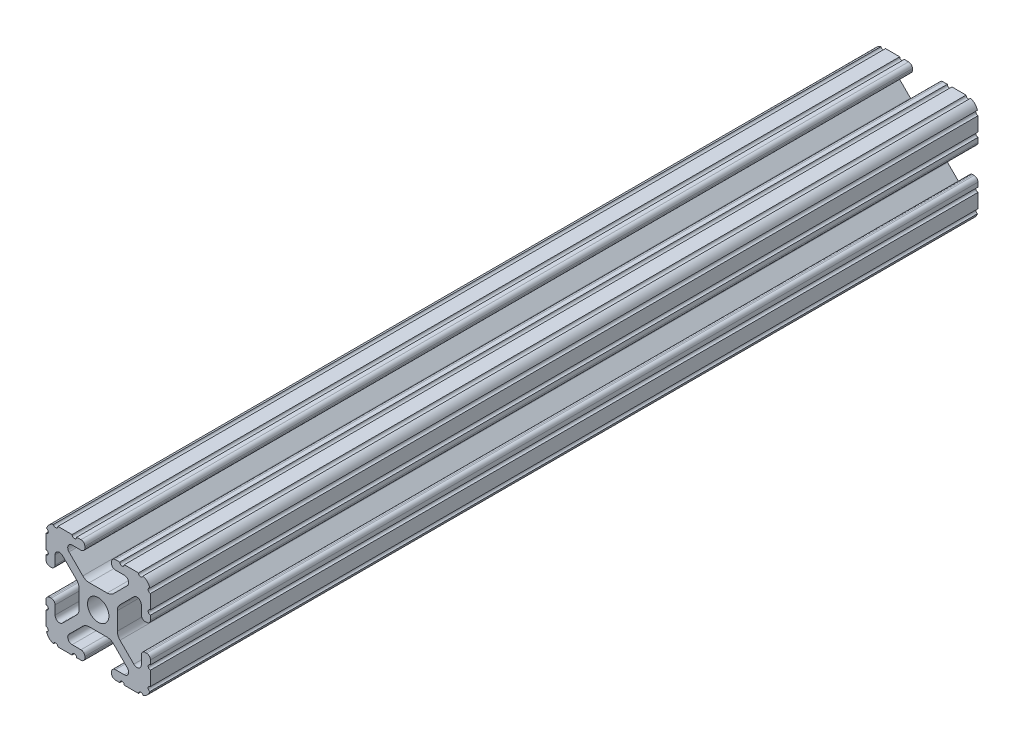
SolidWorks part; units mm, degrees
ref_plane "Front Plane" through (0, 0, 0) normal (0, 0, 1) x (1, 0, 0)
ref_plane "Top Plane" through (0, 0, 0) normal (0, 1, 0) x (1, 0, 0)
ref_plane "Right Plane" through (0, 0, 0) normal (1, 0, 0) x (0, 0, -1)
sketch "Sketch2" plane through (0, 0, 0) normal (0, 0, 1) x (1, 0, 0)
  line L0 (0, 12.7) -> (0, -12.7) construction
  line L1 (-12.7, 0) -> (12.7, 0) construction
  line L2 (3.2512, -12.7) -> (12.7, -12.7)
  line L3 (12.7, -12.7) -> (12.7, -3.2512)
  line L4 (3.2512, -12.7) -> (3.2512, -10.4902)
  line L5 (3.2512, -10.4902) -> (8.9276, -10.4902)
  line L6 (8.9276, -10.4902) -> (3.0856, -4.6482)
  line L7 (0, 0) -> (12.7, -12.7) construction
  line L8 (12.7, -3.2512) -> (10.4902, -3.2512)
  line L9 (10.4902, -3.2512) -> (10.4902, -8.9276)
  line L10 (10.4902, -8.9276) -> (4.6482, -3.0856)
  circle A0 centre (0, 0) radius 2.6035
  arc A1 (6.3485, -10.4902) -> (7.1039, -8.6665) centre (6.3485, -9.4219) ccw construction
  point P8 (0, -4.6482)
  dimension "Center Hole Diameter" = 5.207
  dimension "Rail Height" = 25.4
  dimension "Rail Width" = 25.4
  dimension "T-Slot Width" = 6.5024
  dimension "Slot Inner Width" = 14.8336
  dimension "Thickness" = 2.2098
  dimension "Slot Depth" = 5.842
  dimension "D1" = 2.2098
sketch "Sketch3" plane through (0, 0, 0) normal (1, 0, 0) x (0, 0, -1)
  line L0 (-100.6793, -12.7) -> (100.6793, -12.7) construction
  line L1 (-75.2793, 0) -> (75.2793, 0) construction
  line L2 (100.6793, 0) -> (-100.6793, 0) construction
sketch "Sketch4" plane through (0, 0, 0) normal (0, 0, 1) x (1, 0, 0)
  line L0 (4.1904, -12.7) -> (10.1173, -12.7)
  line L1 (3.2512, -12.7) -> (12.7, -12.7) construction
  line L2 (3.2512, -12.7) -> (3.2512, -10.4902) construction
  line L3 (3.2512, -10.4902) -> (8.9276, -10.4902) construction
  line L4 (3.2512, -11.4294) -> (3.2512, -11.7608)
  line L5 (4.1904, -10.4902) -> (6.3485, -10.4902)
  line L6 (0, -4.6482) -> (2.164, -4.6482)
  line L7 (8.9276, -10.4902) -> (3.0856, -4.6482) construction
  line L8 (3.7373, -5.2999) -> (7.1039, -8.6665)
  line L9 (12.7, -12.7) -> (12.7, -3.2512) construction
  line L10 (10.4902, -8.9276) -> (4.6482, -3.0856) construction
  line L11 (10.4902, -3.2512) -> (10.4902, -8.9276) construction
  line L12 (10.4902, -6.3485) -> (10.4902, -4.1904)
  line L13 (12.7, -3.2512) -> (10.4902, -3.2512) construction
  line L14 (11.4294, -3.2512) -> (11.7608, -3.2512)
  line L15 (12.7, -4.1904) -> (12.7, -10.1173)
  line L16 (8.6665, -7.1039) -> (5.2999, -3.7373)
  line L17 (4.6482, 0) -> (4.6482, -2.164)
  line L18 (-12.7, 0) -> (12.7, 0) construction
  line L19 (0, -4.6482) -> (0, -2.6035)
  line L20 (0, 12.7) -> (0, -12.7) construction
  line L21 (4.6482, 0) -> (2.6035, 0)
  arc A0 (3.2512, -11.7608) -> (4.1904, -12.7) centre (4.1904, -11.7608) ccw
  arc A2 (3.2512, -11.4294) -> (4.1904, -10.4902) centre (4.1904, -11.4294) cw
  arc A3 (6.3485, -10.4902) -> (7.1039, -8.6665) centre (6.3485, -9.4219) ccw
  arc A4 (2.164, -4.6482) -> (3.7373, -5.2999) centre (2.164, -6.8732) cw
  arc A5 (10.1173, -12.7) -> (12.7, -10.1173) centre (10.1173, -10.1173) ccw
  arc A6 (8.6665, -7.1039) -> (10.4902, -6.3485) centre (9.4219, -6.3485) ccw
  arc A7 (10.4902, -4.1904) -> (11.4294, -3.2512) centre (11.4294, -4.1904) cw
  arc A8 (11.7608, -3.2512) -> (12.7, -4.1904) centre (11.7608, -4.1904) cw
  arc A9 (5.2999, -3.7373) -> (4.6482, -2.164) centre (6.8732, -2.164) cw
  circle A10 centre (0, 0) radius 2.6035 construction
  arc A11 (0, -2.6035) -> (2.6035, 0) centre (0, 0) ccw
  dimension "D1" = 2.5827
  dimension "D2" = 2.225
  dimension "D3" = 0.9392
extrude "Boss-Extrude1" add sketch "Sketch4" along normal up to vertex (100.6793 mm away) from vertex at -100.6793 starting at point (0, -12.7, -100.6793)
sketch "Sketch5" plane through (0, 0, 0) normal (0, 0, 1) x (1, 0, 0)
  line L0 (3.2512, -12.7) -> (12.7, -12.7) construction
  line L1 (4.1904, -10.4902) -> (6.3485, -10.4902) construction
  line L3 (0, 0) -> (12.7, -12.7) construction
  line L4 (6.3485, -10.4902) -> (6.3485, -12.7) construction
  line L5 (8.9276, -10.4902) -> (3.0856, -4.6482) construction
  circle A0 centre (10.3562, -12.7) radius 0.5524
  circle A1 centre (5.796, -12.7) radius 0.5524
  circle A2 centre (12.7, -10.3562) radius 0.5524
  circle A3 centre (12.7, -5.796) radius 0.5524
  point P10 (5.2694, -10.4902)
  point P12 (9.4219, -6.3485)
  dimension "D1" = 1.1049
extrude "Cut-Extrude1" cut sketch "Sketch5" against normal through all both and the other way through all
mirror "Mirror1" about plane through (0, 0, 0) normal (1, 0, 0) of bodies 137 134
mirror "Mirror2" about plane through (0, 0, 0) normal (0, 1, 0) of bodies 135
equation "\"D1@Sketch2\"=\"Thickness@Sketch2\""
equation "\"D2@Sketch4\"=\"Slot Inner Width@Sketch2\"*0.15"
equation "\"D1@Sketch4\"=\"D3@Sketch4\"*2.75"
equation "\"D3@Sketch4\"=\"Thickness@Sketch2\"*0.425"
equation "\"D1@Sketch5\"=\"Thickness@Sketch2\"*0.5"
equation "\"D1@Boss-Extrude1\"=\"Length@Sketch3\""
